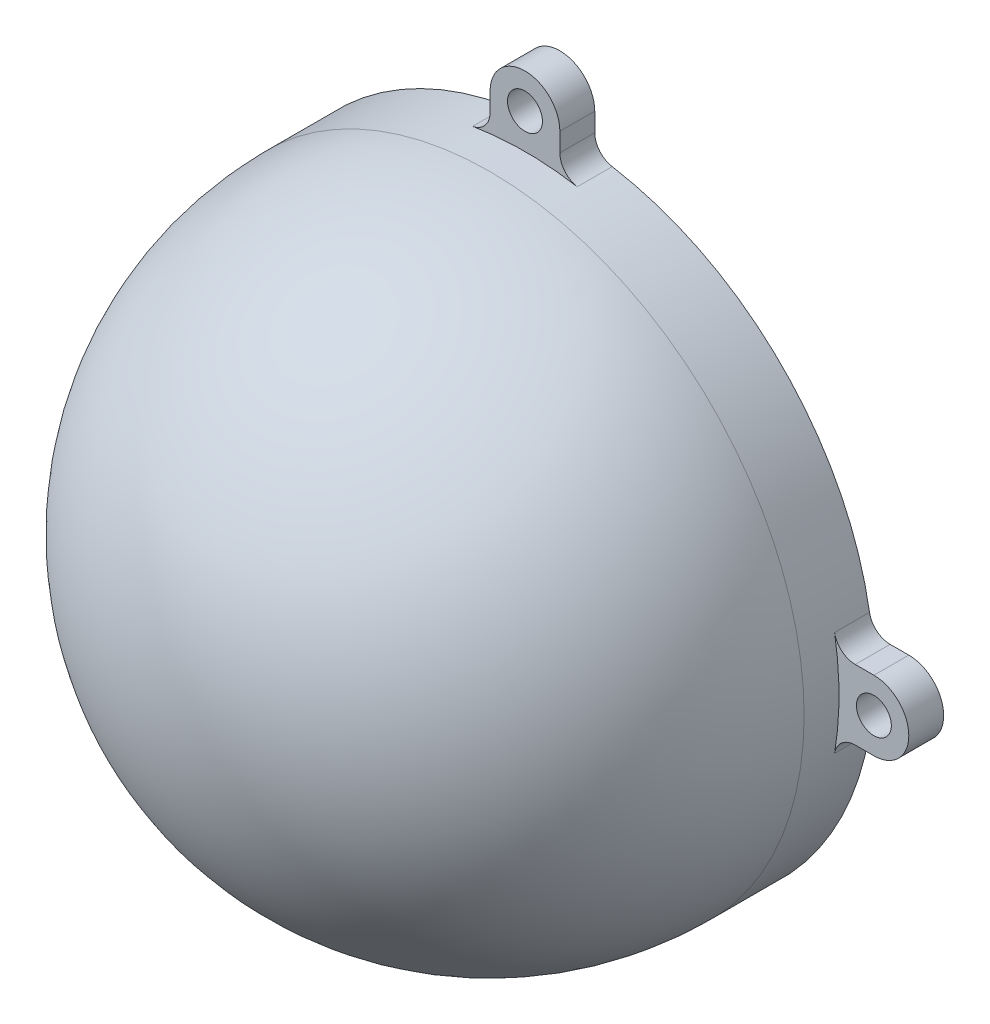
SolidWorks part; units mm, degrees
ref_plane "Front Plane" through (0, 0, 0) normal (0, 0, 1) x (1, 0, 0)
ref_plane "Top Plane" through (0, 0, 0) normal (0, 1, 0) x (1, 0, 0)
ref_plane "Right Plane" through (0, 0, 0) normal (1, 0, 0) x (0, 0, -1)
sketch "Sketch1" plane through (0, 0, 0) normal (0, 0, 1) x (1, 0, 0)
  circle A0 centre (0, 0) radius 42.5
  circle A1 centre (0, 0) radius 45
  dimension "D1" = 85
  dimension "D2" = 90
extrude "Boss-Extrude1" add sketch "Sketch1" along normal blind 10
sketch "Sketch3" plane through (0, 0, 0) normal (1, 0, 0) x (0, 0, -1)
  line L0 (-55, 0) -> (-52.5, 0)
  line L1 (-10, -45) -> (-10, -42.5)
  arc A0 (-10, -45) -> (-55, 0) centre (-10, 0) cw
  arc A1 (-10, -42.5) -> (-52.5, 0) centre (-10, 0) cw
  dimension "D1" = 45
  dimension "D2" = 10
  dimension "D3" = 2.5
revolve "Revolve1" add sketch "Sketch3" angle 360 about L0
sketch "Sketch4" plane through (0, 0, 0) normal (0, 0, 1) x (1, 0, 0)
  line L0 (0, 0) -> (0, 58.3133) construction
  line L1 (5, 44.7214) -> (5, 50)
  line L2 (-5, 50) -> (-5, 44.7214)
  circle A0 centre (0, 0) radius 45 construction
  arc A1 (5, 50) -> (-5, 50) centre (0, 50) ccw
  circle A2 centre (0, 50) radius 2.5
  arc A3 (5, 44.7214) -> (-5, 44.7214) centre (0, 0) ccw
  dimension "D1" = 5
  dimension "D3" = 5
  dimension "D2" = 50
extrude "Boss-Extrude2" add sketch "Sketch4" along normal blind 5
fillet "Fillet1" radius 3 2 edges at (5, 44.7214, 2.5) (-5, 44.7214, 2.5)
pattern_circular "CirPattern1" count 4 over 360 about axis through (0, 0, 0) along (0, 0, 1) of "Boss-Extrude2", "Fillet1"
